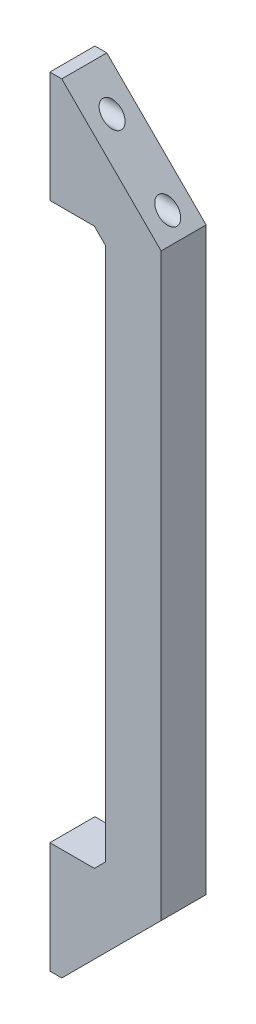
SolidWorks part; units mm, degrees
ref_plane "Plan de face" through (0, 0, 0) normal (0, 0, 1) x (1, 0, 0)
ref_plane "Plan de dessus" through (0, 0, 0) normal (0, 1, 0) x (1, 0, 0)
ref_plane "Plan de droite" through (0, 0, 0) normal (1, 0, 0) x (0, 0, -1)
sketch "Esquisse1" plane through (0, 0, 0) normal (0, 0, 1) x (1, 0, 0)
  line L0 (0, 0) -> (0, 20)
  line L1 (0, 20) -> (8, 20)
  line L2 (8, 20) -> (10, 22)
  line L3 (10, 22) -> (10, 118)
  line L4 (10, 70) -> (0.9132, 70) construction
  line L5 (0, 0) -> (2.1421, 0)
  line L6 (2.1421, 0) -> (20, 17.8579)
  line L7 (20, 17.8579) -> (20, 122.1421)
  line L8 (20, 70) -> (10, 70) construction
  line L9 (2.1421, 140) -> (20, 122.1421)
  line L10 (0, 140) -> (2.1421, 140)
  line L11 (8, 120) -> (10, 118)
  line L12 (0, 120) -> (8, 120)
  line L13 (0, 140) -> (0, 120)
  point P2 (9, 21)
  point P17 (9.1201, 0)
  dimension "D1" = 20
  dimension "D2" = 10
  dimension "D3" = 10
  dimension "D4" = 10
  dimension "D5" = 135
  dimension "D6" = 140
  dimension "D7" = 8
extrude "Boss.-Extru.1" add sketch "Esquisse1" along normal blind 8.1
sketch "Esquisse2" plane through (0, 0, 0) normal (-1, 0, 0) x (0, 0, 1)
  line L0 (4.05, 0) -> (4.05, 20) construction
  line L1 (8.1, 0) -> (0, 0) construction
  line L2 (8.1, 20) -> (0, 20) construction
  line L3 (4.05, 120) -> (4.05, 140) construction
  line L4 (8.1, 120) -> (0, 120) construction
  line L5 (8.1, 140) -> (0, 140) construction
  line L6 (0, 70) -> (8.1, 70) construction
  line L7 (0, 118) -> (0, 22) construction
  line L8 (8.1, 118) -> (8.1, 22) construction
  line L9 (4.05, 10) -> (0, 10) construction
  line L10 (0, 20) -> (0, 0) construction
  line L11 (4.05, 130) -> (0, 130) construction
  circle A0 centre (4.05, 15) radius 1.65
  circle A1 centre (4.05, 5) radius 1.65
  circle A2 centre (4.05, 135) radius 1.65
  circle A3 centre (4.05, 125) radius 1.65
  dimension "D1" = 5
  dimension "D2" = 3.3
extrude "Enlèv. mat.-Extru.1" cut sketch "Esquisse2" against normal through all
